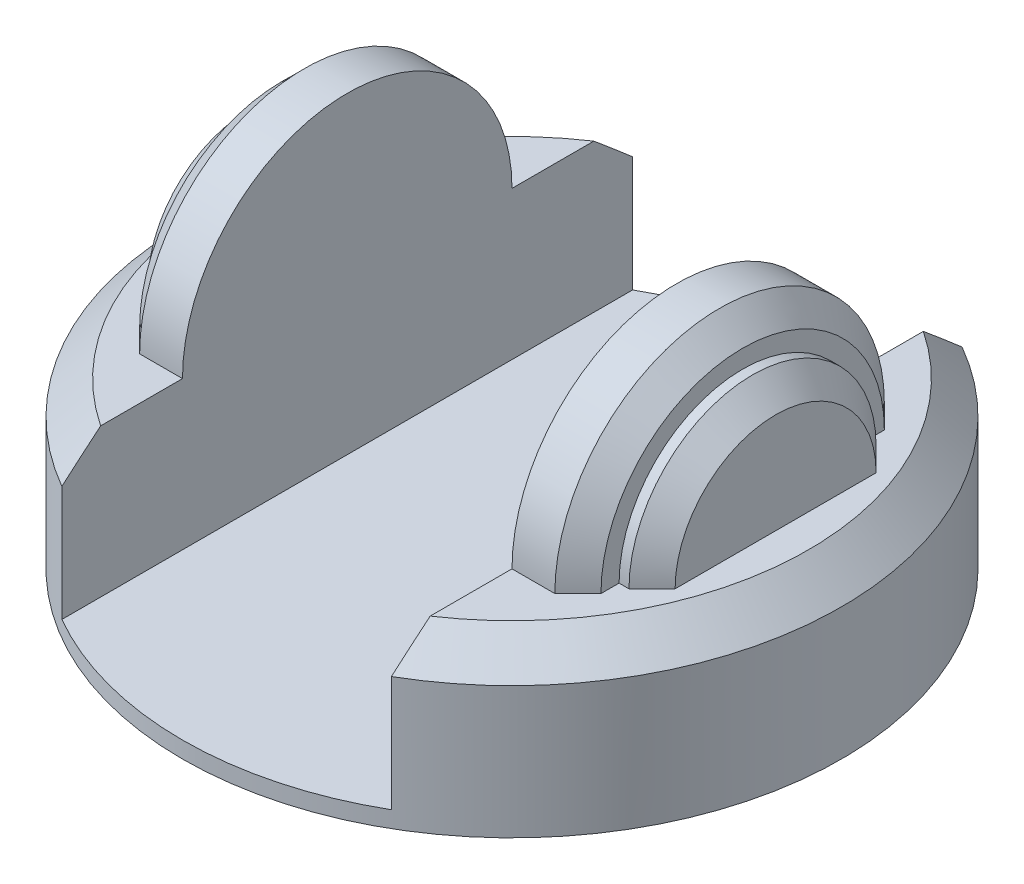
SolidWorks part; units mm, degrees
ref_plane "Front Plane" through (0, 0, 0) normal (0, 0, 1) x (1, 0, 0)
ref_plane "Top Plane" through (0, 0, 0) normal (0, 1, 0) x (1, 0, 0)
ref_plane "Right Plane" through (0, 0, 0) normal (1, 0, 0) x (0, 0, -1)
sketch "Sketch1" plane through (0, 0, 0) normal (0, 1, 0) x (1, 0, 0)
  circle A0 centre (0, 0) radius 100
  dimension "D1" = 200
extrude "Boss-Extrude1" add sketch "Sketch1" along normal blind 50
sketch "Sketch2" plane through (0, 50, 0) normal (0, 1, 0) x (1, 0, 0)
  line L1 (-50, -107.1353) -> (50, -107.1353)
  line L2 (-50, -107.1353) -> (-50, 107.1353)
  line L3 (-50, 107.1353) -> (50, 107.1353)
  line L4 (50, -107.1353) -> (50, 107.1353)
  line L5 (-50, -107.1353) -> (50, 107.1353) construction
  line L6 (-50, 107.1353) -> (50, -107.1353) construction
  point P0 (0, 0)
  dimension "D1" = 100
extrude "Cut-Extrude1" cut sketch "Sketch2" against normal blind 45
sketch "Sketch3" plane through (-50, 0, 0) normal (1, 0, 0) x (0, 0, -1)
  line L0 (0, 50) -> (0, 125.6611) construction
  line L1 (86.6025, 50) -> (-86.6025, 50) construction
  circle A0 centre (0, 50) radius 50
  dimension "D1" = 100
extrude "Boss-Extrude2" add sketch "Sketch3" against normal blind 20
mirror "Mirror1" about plane through (0, 0, 0) normal (1, 0, 0) of "Boss-Extrude2"
sketch "Sketch4" plane through (70, 0, 0) normal (1, 0, 0) x (0, 0, -1)
  line L0 (50, 50) -> (-50, 50) construction
  circle A0 centre (0, 50) radius 37.5
  dimension "D1" = 75
extrude "Boss-Extrude3" add sketch "Sketch4" along normal blind 10
mirror "Mirror2" about plane through (0, 0, 0) normal (1, 0, 0) of "Boss-Extrude3"
chamfer "Chamfer1" distance 10 angle 45 2 edges at (-100, 50, 0) (100, 50, 0)
chamfer "Chamfer2" distance 7 angle 45 4 edges at (-80, 87.5, 0) (-70, 100, 0) (80, 87.5, 0) (70, 100, 0)
